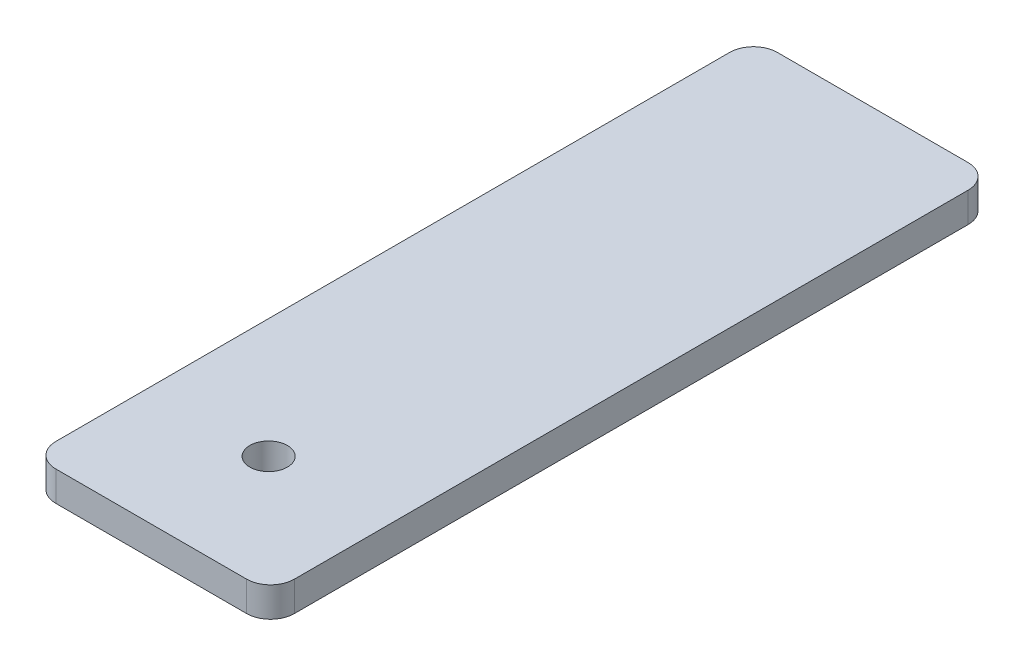
SolidWorks part; units mm, degrees
material "Acrylic (Medium-high impact)"
ref_plane "Front Plane" through (0, 0, 0) normal (0, 0, 1) x (1, 0, 0)
ref_plane "Top Plane" through (0, 0, 0) normal (0, 1, 0) x (1, 0, 0)
ref_plane "Right Plane" through (0, 0, 0) normal (1, 0, 0) x (0, 0, -1)
ref_plane "Plane1" through (0, 0, 0) normal (0, 1, 0) x (1, 0, 0)
sketch "Sketch1" plane through (0, 0, 0) normal (0, 1, 0) x (1, 0, 0)
  line L1 (-26.2811, -20.6088) -> (-0.8811, -20.6088)
  line L2 (-26.2811, -20.6088) -> (-26.2811, 56.2162)
  line L3 (-26.2811, 56.2162) -> (-0.8811, 56.2162)
  line L4 (-0.8811, -20.6088) -> (-0.8811, 56.2162)
  dimension "D1" = 76.825
  dimension "D2" = 25.4
extrude "Boss-Extrude1" add sketch "Sketch1" along normal blind 3.175
sketch "Sketch2" plane through (0, 3.175, 0) normal (0, 1, 0) x (1, 0, 0)
  line L0 (-26.2811, -20.6088) -> (-0.8811, -20.6088) construction
  line L1 (-26.2811, 56.2162) -> (-26.2811, -20.6088) construction
  circle A0 centre (-13.5811, -8.1088) radius 2
  dimension "D2" = 4
  dimension "D1" = 12.5
  dimension "D3" = 12.7
extrude "Cut-Extrude1" cut sketch "Sketch2" against normal through all
fillet "Fillet1" radius 2.54 4 edges at (-26.2811, 1.5875, -56.2162) (-0.8811, 1.5875, -56.2162) (-0.8811, 1.5875, 20.6088) (-26.2811, 1.5875, 20.6088)
